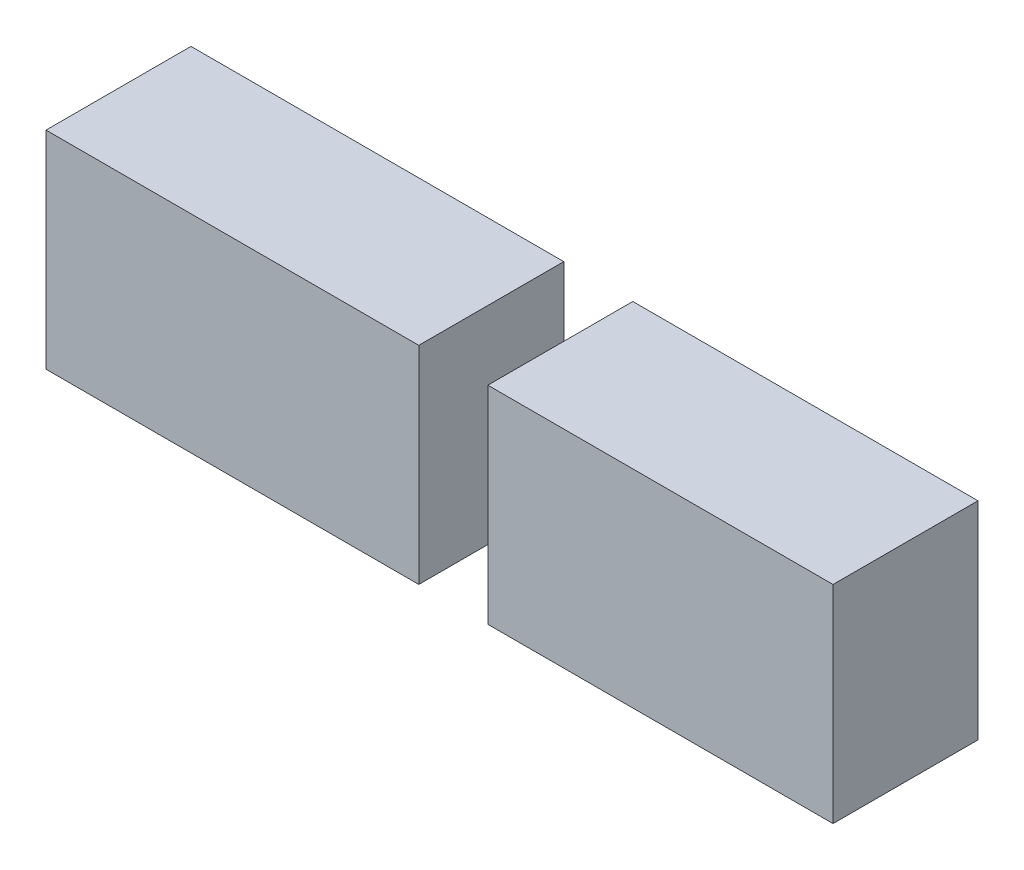
SolidWorks part; units mm, degrees
ref_plane "Plan de face" through (0, 0, 0) normal (0, 0, 1) x (1, 0, 0)
ref_plane "Plan de dessus" through (0, 0, 0) normal (0, 1, 0) x (1, 0, 0)
ref_plane "Plan de droite" through (0, 0, 0) normal (1, 0, 0) x (0, 0, -1)
sketch "Esquisse1" plane through (0, 0, 0) normal (0, 0, 1) x (1, 0, 0)
  line L1 (0, 0) -> (50, 0)
  line L2 (0, 0) -> (0, 30)
  line L3 (0, 30) -> (50, 30)
  line L4 (50, 0) -> (50, 30)
  dimension "D1" = 50
  dimension "D2" = 30
extrude "Boss.-Extru.1" add sketch "Esquisse1" along normal blind 21
ref_plane "Plan1" through (-10, 0, 0) normal (-1, 0, 0) x (0, 0, 1)
sketch "Esquisse3" plane through (-10, 0, 0) normal (-1, 0, 0) x (0, 0, 1)
  line L0 (21, 30) -> (0, 30) construction
  line L1 (21, 30) -> (0, 30)
  line L2 (21, 30) -> (21, 0)
  line L3 (21, 0) -> (0, 0)
  line L4 (0, 30) -> (0, 0)
  line L12 (0, 0) -> (0, 30) construction
  dimension "21" = 21
extrude "Boss.-Extru.3" add sketch "Esquisse3" along normal blind 54 separate body
